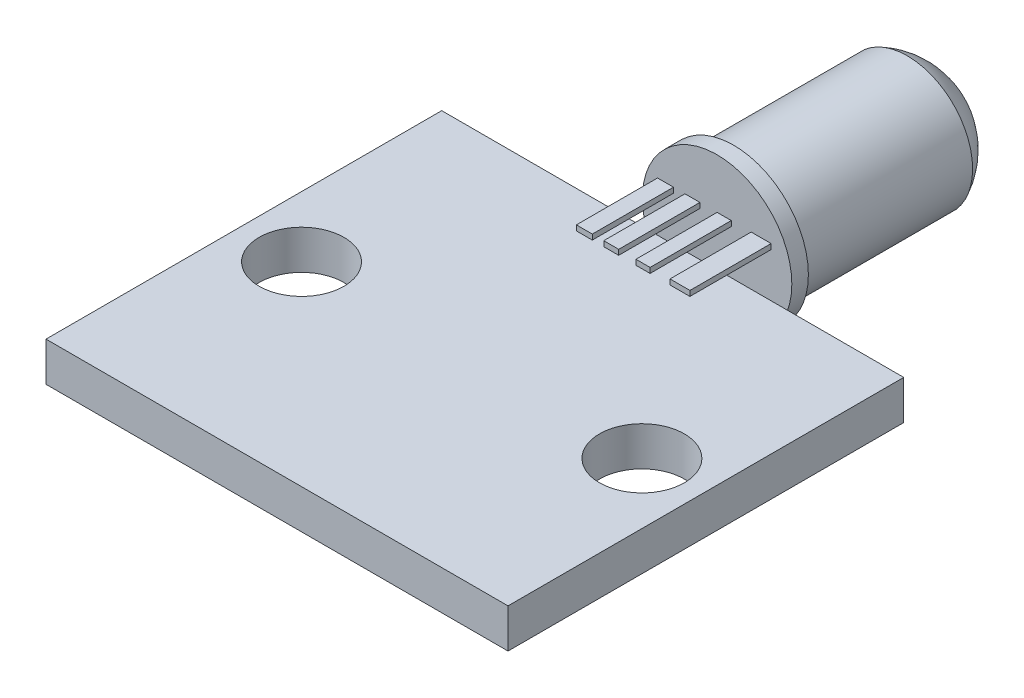
SolidWorks part; units mm, degrees
ref_plane "Front Plane" through (0, 0, 0) normal (0, 0, 1) x (1, 0, 0)
ref_plane "Top Plane" through (0, 0, 0) normal (0, 1, 0) x (1, 0, 0)
ref_plane "Right Plane" through (0, 0, 0) normal (1, 0, 0) x (0, 0, -1)
sketch "Sketch1" plane through (0, 0, 0) normal (0, 1, 0) x (1, 0, 0)
  line L0 (0, 0) -> (0, 7.58) construction
  line L1 (8.85, 7.58) -> (-8.85, 7.58)
  line L2 (8.85, 7.58) -> (8.85, -7.58)
  line L3 (8.85, -7.58) -> (-8.85, -7.58)
  line L4 (-8.85, 7.58) -> (-8.85, -7.58)
  line L5 (8.85, 7.58) -> (-8.85, -7.58) construction
  line L6 (8.85, -7.58) -> (-8.85, 7.58) construction
  circle A0 centre (-6.52, -0.12) radius 1.625
  circle A1 centre (6.52, -0.12) radius 1.625
  point P0 (0, 0)
  dimension "D3" = 7.7
  dimension "D4" = 2.33
  dimension "D5" = 3.25
  dimension "D1" = 15.16
  dimension "D2" = 17.7
extrude "Boss-Extrude1" add sketch "Sketch1" along normal mid plane 1.5
sketch "Sketch2" plane through (0, 0, 0) normal (0, 1, 0) x (1, 0, 0)
  line L0 (0, 0) -> (0, 11.7392) construction
  line L1 (0, 9.28) -> (0, 18.13)
  line L2 (-2.5, 16.5685) -> (-2.5, 9.9146)
  line L3 (-2.5, 9.9146) -> (-2.8625, 9.9146)
  line L4 (-2.8625, 9.9146) -> (-2.8625, 9.28)
  line L5 (-2.8625, 9.28) -> (0, 9.28)
  line L6 (8.85, 7.58) -> (-8.85, 7.58) construction
  arc A0 (0, 18.13) -> (-2.5, 16.5685) centre (0, 15.348) ccw
  dimension "D1" = 5
  dimension "D2" = 8.85
  dimension "D3" = 1.7
revolve "Revolve1" add sketch "Sketch2" angle 360 about L0
sketch "Sketch3" plane through (0, 0.75, 0) normal (0, 1, 0) x (1, 0, 0)
  line L0 (-2.8625, 9.28) -> (2.8625, 9.28) construction
  line L1 (-2.2812, 9.28) -> (-1.6706, 9.28)
  line L2 (-2.2812, 9.28) -> (-2.2812, 6.1695)
  line L3 (-2.2812, 6.1695) -> (-1.6706, 6.1695)
  line L4 (-1.6706, 9.28) -> (-1.6706, 6.1695)
  line L6 (-1.2318, 9.28) -> (-0.6594, 9.28)
  line L7 (-1.2318, 9.28) -> (-1.2318, 6.1695)
  line L8 (-1.2318, 6.1695) -> (-0.6594, 6.1695)
  line L9 (-0.6594, 9.28) -> (-0.6594, 6.1695)
  line L10 (0, 9.28) -> (0.5427, 9.28)
  line L11 (0, 9.28) -> (0, 6.1695)
  line L12 (0, 6.1695) -> (0.5427, 6.1695)
  line L13 (0.5427, 9.28) -> (0.5427, 6.1695)
  line L14 (1.3059, 9.28) -> (2.0692, 9.28)
  line L15 (1.3059, 9.28) -> (1.3059, 6.1695)
  line L16 (1.3059, 6.1695) -> (2.0692, 6.1695)
  line L17 (2.0692, 9.28) -> (2.0692, 6.1695)
extrude "Boss-Extrude2" add sketch "Sketch3" along normal blind 0.2
